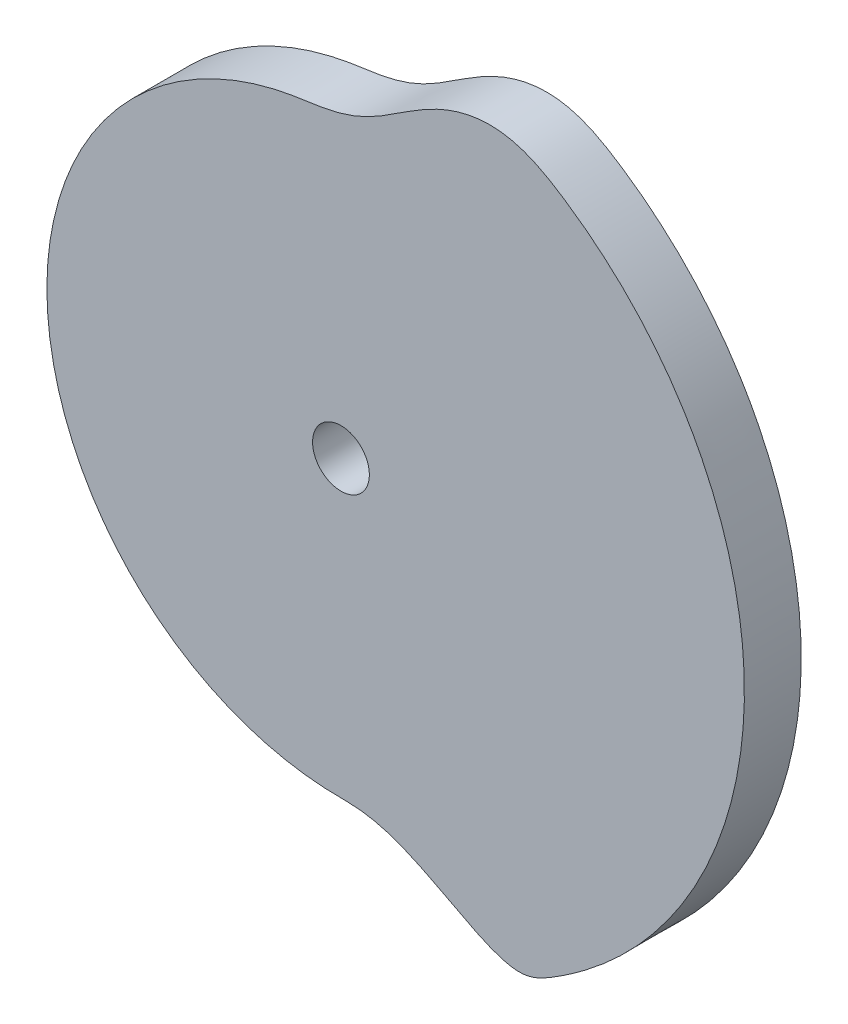
SolidWorks part; units mm, degrees
ref_plane "前视基准面" through (0, 0, 0) normal (0, 0, 1) x (1, 0, 0)
ref_plane "上视基准面" through (0, 0, 0) normal (0, 1, 0) x (1, 0, 0)
ref_plane "右视基准面" through (0, 0, 0) normal (1, 0, 0) x (0, 0, -1)
other "Configuration Table"
curve "曲线1"
sketch "草图2" plane through (0, 0, 0) normal (0, 0, 1) x (1, 0, 0)
  spline S0 degree 3 poles (121.2946, 73.8631) (120.6455, 74.9188) (119.987, 75.9687) (119.3211, 77.0105) (118.6446, 78.0488) (117.959, 79.0812) (117.2643, 80.1075) (116.5609, 81.1278) (115.8485, 82.1419) (115.1271, 83.1496) (114.3973, 84.1512) (113.6585, 85.1463) (112.9111, 86.1349) (112.1552, 87.1169) (111.3907, 88.0923) (110.6177, 89.061) (109.8363, 90.023) (109.0465, 90.978) (108.2485, 91.9262) (107.4421, 92.8673) (106.6277, 93.8014) (105.805, 94.7283) (104.9743, 95.648) (104.1356, 96.5604) (103.2891, 97.4655) (102.4346, 98.3631) (101.5723, 99.2532) (100.7023, 100.1359) (99.8246, 101.0108) (98.9394, 101.8781) (98.0465, 102.7376) (97.1463, 103.5893) (96.2386, 104.4331) (95.3236, 105.2689) (94.4013, 106.0968) (93.4719, 106.9166) (92.5353, 107.7282) (91.5916, 108.5315) (90.6412, 109.3268) (89.6836, 110.1136) (88.7193, 110.892) (87.7483, 111.662) (86.7704, 112.4234) (85.7861, 113.1765) (84.7952, 113.9208) (83.7978, 114.6563) (82.7941, 115.3833) (81.7841, 116.1014) (80.7677, 116.8105) (79.7453, 117.511) (78.7168, 118.2024) (77.6846, 118.8834) (76.653, 119.5509) (75.6258, 120.201) (74.6039, 120.8306) (73.5866, 121.4387) (72.573, 122.0241) (71.562, 122.5858) (70.5529, 123.1229) (69.5449, 123.6347) (68.5369, 124.12) (67.5284, 124.5788) (66.5183, 125.0099) (65.5061, 125.413) (64.4908, 125.7876) (63.4718, 126.1332) (62.4483, 126.4492) (61.4197, 126.7353) (60.3854, 126.9914) (59.3447, 127.2164) (58.2973, 127.4105) (57.2429, 127.5731) (56.1811, 127.7038) (55.1118, 127.8021) (54.0351, 127.8678) (52.9511, 127.9005) (51.86, 127.8999) (50.7622, 127.866) (49.6584, 127.7981) (48.5492, 127.6967) (47.4353, 127.5614) (46.3177, 127.3927) (45.1974, 127.1905) (44.0754, 126.9555) (42.9528, 126.6879) (41.8308, 126.3884) (40.7104, 126.058) (39.5929, 125.6974) (38.4793, 125.3076) (37.3706, 124.8899) (36.2678, 124.4455) (35.1718, 123.9756) (34.0833, 123.4821) (33.0031, 122.9662) (31.9315, 122.4295) (30.8689, 121.874) (29.8155, 121.3011) (28.7713, 120.7128) (27.7361, 120.1108) (26.7097, 119.4966) (25.6913, 118.8725) (24.6806, 118.2398) (23.6763, 117.6005) (22.6776, 116.9563) (21.6831, 116.3089) (20.6917, 115.6599) (19.7016, 115.0113) (18.7117, 114.3644) (17.7202, 113.7213) (16.7253, 113.0835) (15.7256, 112.453) (14.7196, 111.8316) (13.7058, 111.2211) (12.6831, 110.6237) (11.6506, 110.041) (10.6076, 109.4755) (9.5539, 108.9289) (8.4895, 108.4033) (7.4151, 107.9003) (6.3314, 107.4216) (5.2398, 106.9684) (4.1418, 106.5418) (3.0392, 106.1422) (1.934, 105.77) (0.8282, 105.4249) (-0.2761, 105.1061) (-1.3771, 104.8128) (-2.4728, 104.5433) (-3.5617, 104.2963) (-4.6422, 104.07) (-5.713, 103.8619) (-6.7729, 103.6702) (-7.8209, 103.4928) (-8.856, 103.3273) (-9.8773, 103.1717) (-10.8842, 103.0236) (-11.8756, 102.881) (-12.851, 102.7423) (-13.8092, 102.6049) (-14.7496, 102.4678) (-15.6712, 102.3287) (-16.5763, 102.186) (-17.4706, 102.0368) (-18.3604, 101.8805) (-19.2488, 101.7164) (-20.1356, 101.5444) (-21.021, 101.365) (-21.9048, 101.1777) (-22.7869, 100.9827) (-23.6673, 100.78) (-24.5458, 100.5695) (-25.4225, 100.3516) (-26.2973, 100.1258) (-27.17, 99.8926) (-28.0407, 99.6516) (-28.9092, 99.4032) (-29.7756, 99.1472) (-30.6396, 98.8834) (-31.5014, 98.6124) (-32.3607, 98.3338) (-33.2176, 98.0475) (-34.072, 97.754) (-34.9238, 97.4529) (-35.7728, 97.1445) (-36.6192, 96.8285) (-37.4628, 96.5054) (-38.3035, 96.1747) (-39.1413, 95.8368) (-39.9762, 95.4917) (-40.8079, 95.1391) (-41.6366, 94.7794) (-42.4621, 94.4124) (-43.2844, 94.0383) (-44.1034, 93.657) (-44.919, 93.2685) (-45.7312, 92.8729) (-46.54, 92.4704) (-47.3451, 92.0606) (-48.1467, 91.6441) (-48.9446, 91.2205) (-49.7387, 90.7898) (-50.5291, 90.3524) (-51.3156, 89.9079) (-52.0984, 89.4568) (-52.877, 88.9986) (-53.6516, 88.5338) (-54.4222, 88.0624) (-55.1886, 87.584) (-55.9508, 87.0991) (-56.7087, 86.6075) (-57.4623, 86.1093) (-58.2116, 85.6046) (-58.9565, 85.0934) (-59.6967, 84.5756) (-60.4325, 84.0515) (-61.1637, 83.5209) (-61.8902, 82.9839) (-62.612, 82.4407) (-63.329, 81.8911) (-64.0413, 81.3355) (-64.7486, 80.7734) (-65.451, 80.2053) (-66.1484, 79.6311) (-66.8409, 79.0509) (-67.5282, 78.4646) (-68.2103, 77.8723) (-68.8873, 77.2741) (-69.559, 76.67) (-70.2254, 76.0601) (-70.8864, 75.4443) (-71.5421, 74.8229) (-72.1923, 74.1957) (-72.837, 73.5629) (-73.4762, 72.9245) (-74.1098, 72.2805) (-74.7377, 71.631) (-75.36, 70.9761) (-75.9765, 70.3158) (-76.5872, 69.6501) (-77.1921, 68.9791) (-77.7911, 68.3029) (-78.3842, 67.6215) (-78.9713, 66.9348) (-79.5524, 66.2432) (-80.1274, 65.5464) (-80.6964, 64.8446) (-81.2593, 64.138) (-81.8158, 63.4264) (-82.3662, 62.7101) (-82.9102, 61.9889) (-83.448, 61.263) (-83.9795, 60.5324) (-84.5046, 59.7973) (-85.0231, 59.0576) (-85.5353, 58.3134) (-86.0408, 57.5647) (-86.54, 56.8118) (-87.0324, 56.0543) (-87.5183, 55.2928) (-87.9974, 54.5269) (-88.4699, 53.7569) (-88.9358, 52.9829) (-89.3946, 52.2047) (-89.8469, 51.4227) (-90.2922, 50.6366) (-90.7305, 49.8467) (-91.1622, 49.0532) (-91.5866, 48.2557) (-92.0044, 47.4546) (-92.415, 46.6499) (-92.8185, 45.8417) (-93.215, 45.03) (-93.6044, 44.2148) (-93.9867, 43.3963) (-94.3618, 42.5744) (-94.7298, 41.7494) (-95.0905, 40.9211) (-95.4439, 40.0897) (-95.7901, 39.2553) (-96.1291, 38.4179) (-96.4607, 37.5776) (-96.7849, 36.7344) (-97.1018, 35.8884) (-97.4114, 35.0397) (-97.7133, 34.1882) (-98.0079, 33.3342) (-98.2952, 32.4777) (-98.5749, 31.6187) (-98.8469, 30.7572) (-99.1117, 29.8935) (-99.3688, 29.0275) (-99.6183, 28.1592) (-99.8602, 27.2888) (-100.0944, 26.4163) (-100.3214, 25.5419) (-100.5402, 24.6654) (-100.7517, 23.7871) (-100.9555, 22.907) (-101.1515, 22.0251) (-101.3399, 21.1416) (-101.5205, 20.2564) (-101.6934, 19.3698) (-101.8586, 18.4816) (-102.016, 17.592) (-102.1656, 16.7011) (-102.3074, 15.8089) (-102.4415, 14.9155) (-102.5678, 14.021) (-102.6862, 13.1254) (-102.7968, 12.2288) (-102.8996, 11.3313) (-102.9946, 10.4329) (-103.0817, 9.5337) (-103.161, 8.6338) (-103.2324, 7.7332) (-103.296, 6.8321) (-103.3517, 5.9304) (-103.3995, 5.0283) (-103.4394, 4.1258) (-103.4715, 3.2229) (-103.4957, 2.3199) (-103.512, 1.4166) (-103.5204, 0.5133) (-103.5209, -0.3901) (-103.5137, -1.2935) (-103.4983, -2.1967) (-103.4752, -3.0999) (-103.4442, -4.0027) (-103.4055, -4.9053) (-103.3586, -5.8075) (-103.304, -6.7092) (-103.2415, -7.6104) (-103.1712, -8.5111) (-103.093, -9.4111) (-103.0068, -10.3103) (-102.9132, -11.2089) (-102.8113, -12.1065) (-102.7018, -13.0033) (-102.5844, -13.899) (-102.4592, -14.7937) (-102.3262, -15.6872) (-102.1854, -16.5795) (-102.0368, -17.4706) (-101.8805, -18.3604) (-101.7164, -19.2488) (-101.5444, -20.1356) (-101.365, -21.021) (-101.1777, -21.9048) (-100.9827, -22.7869) (-100.78, -23.6673) (-100.5695, -24.5458) (-100.3516, -25.4225) (-100.1258, -26.2973) (-99.8926, -27.17) (-99.6516, -28.0407) (-99.4032, -28.9092) (-99.1472, -29.7756) (-98.8834, -30.6396) (-98.6124, -31.5014) (-98.3338, -32.3607) (-98.0475, -33.2176) (-97.754, -34.072) (-97.4529, -34.9238) (-97.1445, -35.7728) (-96.8285, -36.6192) (-96.5054, -37.4628) (-96.1747, -38.3035) (-95.8368, -39.1413) (-95.4917, -39.9762) (-95.1391, -40.8079) (-94.7794, -41.6366) (-94.4124, -42.4621) (-94.0383, -43.2844) (-93.657, -44.1034) (-93.2685, -44.919) (-92.8729, -45.7312) (-92.4704, -46.54) (-92.0606, -47.3451) (-91.6441, -48.1467) (-91.2205, -48.9446) (-90.7898, -49.7387) (-90.3524, -50.5291) (-89.9079, -51.3156) (-89.4568, -52.0984) (-88.9986, -52.877) (-88.5338, -53.6516) (-88.0624, -54.4222) (-87.584, -55.1886) (-87.0991, -55.9508) (-86.6075, -56.7087) (-86.1093, -57.4623) (-85.6046, -58.2116) (-85.0934, -58.9565) (-84.5756, -59.6967) (-84.0515, -60.4325) (-83.5209, -61.1637) (-82.9839, -61.8902) (-82.4407, -62.612) (-81.8911, -63.329) (-81.3355, -64.0413) (-80.7734, -64.7486) (-80.2053, -65.451) (-79.6311, -66.1484) (-79.0509, -66.8409) (-78.4646, -67.5282) (-77.8723, -68.2103) (-77.2741, -68.8873) (-76.67, -69.559) (-76.0601, -70.2254) (-75.4443, -70.8864) (-74.8229, -71.5421) (-74.1957, -72.1923) (-73.5629, -72.837) (-72.9245, -73.4762) (-72.2805, -74.1098) (-71.631, -74.7377) (-70.9761, -75.36) (-70.3158, -75.9765) (-69.6501, -76.5872) (-68.9791, -77.1921) (-68.3029, -77.7911) (-67.6215, -78.3842) (-66.9348, -78.9713) (-66.2432, -79.5524) (-65.5464, -80.1274) (-64.8446, -80.6964) (-64.138, -81.2593) (-63.4264, -81.8158) (-62.7101, -82.3662) (-61.9889, -82.9102) (-61.263, -83.448) (-60.5324, -83.9795) (-59.7973, -84.5046) (-59.0576, -85.0231) (-58.3134, -85.5353) (-57.5647, -86.0408) (-56.8118, -86.54) (-56.0543, -87.0324) (-55.2928, -87.5183) (-54.5269, -87.9974) (-53.7569, -88.4699) (-52.9829, -88.9358) (-52.2047, -89.3946) (-51.4227, -89.8469) (-50.6366, -90.2922) (-49.8467, -90.7305) (-49.0532, -91.1622) (-48.2557, -91.5866) (-47.4546, -92.0044) (-46.6499, -92.415) (-45.8417, -92.8185) (-45.03, -93.215) (-44.2148, -93.6044) (-43.3963, -93.9867) (-42.5744, -94.3618) (-41.7494, -94.7298) (-40.9211, -95.0905) (-40.0897, -95.4439) (-39.2553, -95.7901) (-38.4179, -96.1291) (-37.5776, -96.4607) (-36.7344, -96.7849) (-35.8884, -97.1018) (-35.0397, -97.4114) (-34.1882, -97.7133) (-33.3342, -98.0079) (-32.4777, -98.2952) (-31.6187, -98.5749) (-30.7572, -98.8469) (-29.8935, -99.1117) (-29.0275, -99.3688) (-28.1592, -99.6183) (-27.2888, -99.8602) (-26.4163, -100.0944) (-25.5419, -100.3214) (-24.6654, -100.5402) (-23.7871, -100.7517) (-22.907, -100.9555) (-22.0251, -101.1515) (-21.1416, -101.3399) (-20.2564, -101.5205) (-19.3698, -101.6934) (-18.4816, -101.8586) (-17.592, -102.016) (-16.7011, -102.1656) (-15.8089, -102.3074) (-14.9155, -102.4415) (-14.021, -102.5678) (-13.1254, -102.6862) (-12.2288, -102.7968) (-11.3313, -102.8996) (-10.4329, -102.9946) (-9.5337, -103.0817) (-8.6338, -103.161) (-7.7332, -103.2324) (-6.8321, -103.296) (-5.9304, -103.3517) (-5.0283, -103.3995) (-4.1258, -103.4394) (-3.2229, -103.4715) (-2.3198, -103.4957) (-1.4052, -103.5122) (-0.4564, -103.5209) (0.5491, -103.5283) (1.6222, -103.5409) (2.7614, -103.5661) (3.9634, -103.6121) (5.2237, -103.6864) (6.5366, -103.7962) (7.8958, -103.948) (9.2947, -104.1462) (10.7272, -104.3947) (12.1879, -104.6952) (13.6722, -105.0488) (15.1768, -105.4551) (16.6992, -105.9135) (18.2382, -106.4221) (19.7925, -106.9793) (21.3618, -107.583) (22.9456, -108.2304) (24.5433, -108.9189) (26.154, -109.6452) (27.7765, -110.4061) (29.4094, -111.1972) (31.0505, -112.0146) (32.6973, -112.8533) (34.3468, -113.7082) (35.9959, -114.5733) (37.6409, -115.4431) (39.2779, -116.3111) (40.9029, -117.1706) (42.5114, -118.015) (44.0992, -118.8375) (45.6616, -119.6312) (47.1943, -120.3893) (48.6924, -121.1059) (50.1516, -121.7751) (51.5677, -122.3911) (52.9363, -122.9502) (54.2536, -123.4484) (55.5163, -123.8834) (56.7218, -124.2542) (57.8685, -124.5605) (58.9557, -124.8042) (59.9847, -124.9871) (60.9583, -125.1126) (61.881, -125.1847) (62.7595, -125.2064) (63.6017, -125.1814) (64.4169, -125.1118) (65.215, -124.9988) (66.0056, -124.8422) (66.7979, -124.6412) (67.6, -124.3941) (68.4184, -124.0987) (69.2585, -123.7536) (70.1244, -123.3575) (71.0191, -122.9101) (71.9451, -122.412) (72.9045, -121.8653) (73.8993, -121.2724) (74.9241, -120.6421) (75.9663, -119.9886) (77.0104, -119.3211) (78.0488, -118.6446) (79.0812, -117.959) (80.1075, -117.2643) (81.1278, -116.5609) (82.1419, -115.8485) (83.1496, -115.1271) (84.1512, -114.3973) (85.1463, -113.6585) (86.1349, -112.9111) (87.1169, -112.1552) (88.0923, -111.3907) (89.061, -110.6177) (90.023, -109.8363) (90.978, -109.0465) (91.9262, -108.2485) (92.8673, -107.4421) (93.8014, -106.6277) (94.7283, -105.805) (95.648, -104.9743) (96.5604, -104.1356) (97.4655, -103.2891) (98.3631, -102.4346) (99.2532, -101.5723) (100.1359, -100.7023) (101.0108, -99.8246) (101.8781, -98.9394) (102.7376, -98.0465) (103.5893, -97.1463) (104.4331, -96.2386) (105.2689, -95.3236) (106.0968, -94.4013) (106.9166, -93.4719) (107.7282, -92.5353) (108.5315, -91.5916) (109.3268, -90.6412) (110.1136, -89.6836) (110.892, -88.7193) (111.662, -87.7483) (112.4234, -86.7704) (113.1765, -85.7861) (113.9208, -84.7952) (114.6563, -83.7978) (115.3833, -82.7941) (116.1014, -81.784) (116.8106, -80.7677) (117.511, -79.7453) (118.2024, -78.7168) (118.8848, -77.6823) (119.5582, -76.6419) (120.2224, -75.5956) (120.8776, -74.5436) (121.5234, -73.4859) (122.1602, -72.4227) (122.7874, -71.3539) (123.4055, -70.2797) (124.014, -69.2001) (124.6133, -68.1153) (125.2029, -67.0252) (125.7829, -65.93) (126.3536, -64.8299) (126.9145, -63.7248) (127.4659, -62.6149) (128.0073, -61.5002) (128.5391, -60.3808) (129.0611, -59.2567) (129.5733, -58.1283) (130.0757, -56.9953) (130.568, -55.858) (131.0506, -54.7165) (131.5231, -53.5708) (131.9856, -52.421) (132.438, -51.2672) (132.8802, -50.1095) (133.3126, -48.9481) (133.7346, -47.7828) (134.1465, -46.614) (134.5482, -45.4416) (134.9396, -44.2657) (135.3207, -43.0864) (135.6916, -41.9039) (136.0521, -40.7182) (136.4022, -39.5294) (136.7421, -38.3376) (137.0713, -37.1428) (137.3902, -35.9453) (137.6988, -34.745) (137.9966, -33.542) (138.2842, -32.3365) (138.5611, -31.1285) (138.8273, -29.9182) (139.0832, -28.7056) (139.3284, -27.4907) (139.563, -26.2738) (139.787, -25.0549) (140.0002, -23.8341) (140.203, -22.6115) (140.3949, -21.3871) (140.5762, -20.1612) (140.7468, -18.9337) (140.9067, -17.7047) (141.0558, -16.4744) (141.1942, -15.2429) (141.3218, -14.0102) (141.4387, -12.7764) (141.5448, -11.5416) (141.6402, -10.306) (141.7247, -9.0695) (141.7984, -7.8324) (141.8614, -6.5948) (141.9135, -5.3566) (141.9549, -4.1179) (141.9854, -2.879) (142.0051, -1.6398) (142.014, -0.4005) (142.0121, 0.8388) (141.9994, 2.078) (141.9759, 3.3171) (141.9415, 4.5559) (141.8963, 5.7944) (141.8404, 7.0324) (141.7736, 8.2699) (141.696, 9.5068) (141.6077, 10.743) (141.5085, 11.9783) (141.3986, 13.2128) (141.2779, 14.4462) (141.1465, 15.6785) (141.0043, 16.9096) (140.8514, 18.1394) (140.6876, 19.3679) (140.5134, 20.5949) (140.3283, 21.8203) (140.1325, 23.044) (139.9261, 24.266) (139.709, 25.4861) (139.4813, 26.7043) (139.243, 27.9205) (138.9939, 29.1346) (138.7345, 30.3464) (138.4644, 31.5559) (138.1836, 32.763) (137.8926, 33.9676) (137.5908, 35.1697) (137.2788, 36.369) (136.9561, 37.5656) (136.623, 38.7593) (136.2797, 39.9501) (135.9258, 41.1378) (135.5616, 42.3224) (135.1871, 43.5038) (134.8025, 44.6819) (134.4073, 45.8565) (134.002, 47.0277) (133.5865, 48.1953) (133.1609, 49.3592) (132.7251, 50.5193) (132.2792, 51.6756) (131.8231, 52.828) (131.3572, 53.9764) (130.8812, 55.1206) (130.3951, 56.2606) (129.8992, 57.3964) (129.3933, 58.5277) (128.8777, 59.6547) (128.3522, 60.7771) (127.8169, 61.8948) (127.272, 63.0079) (126.7173, 64.1161) (126.1529, 65.2195) (125.579, 66.3179) (124.9955, 67.4112) (124.4025, 68.4995) (123.8, 69.5825) (123.188, 70.6601) (122.5668, 71.7324) (121.9361, 72.7993) (121.2946, 73.8631) (120.6455, 74.9188) (119.987, 75.9687) knots -0.004803 -0.003206 -0.001609 0 0.001586 0.003183 0.004781 0.006378 0.007975 0.009573 0.01117 0.012767 0.014364 0.015962 0.017559 0.019156 0.020754 0.022351 0.023948 0.025546 0.027143 0.02874 0.030338 0.031935 0.033532 0.03513 0.036727 0.038324 0.039922 0.041519 0.043116 0.044713 0.046311 0.047908 0.049505 0.051103 0.0527 0.054297 0.055895 0.057492 0.059089 0.060687 0.062284 0.063881 0.065478 0.067076 0.068673 0.07027 0.071868 0.073465 0.075062 0.07666 0.078257 0.079854 0.081441 0.083008 0.084555 0.086082 0.08759 0.089081 0.090554 0.09201 0.093452 0.094879 0.096294 0.097698 0.099092 0.100478 0.101858 0.103233 0.104606 0.105977 0.107349 0.108724 0.110102 0.111485 0.112875 0.114272 0.115678 0.117093 0.118518 0.119954 0.1214 0.122856 0.124323 0.125801 0.127288 0.128785 0.130291 0.131804 0.133325 0.134852 0.136385 0.137922 0.139463 0.141006 0.142551 0.144096 0.145642 0.147187 0.148731 0.150273 0.151812 0.153349 0.154883 0.156415 0.157944 0.159472 0.160997 0.162521 0.164044 0.165567 0.16709 0.168614 0.170139 0.171666 0.173194 0.174723 0.176253 0.177783 0.179313 0.18084 0.182364 0.183883 0.185395 0.186898 0.188391 0.189873 0.191342 0.192797 0.194236 0.195659 0.197065 0.198454 0.199824 0.201175 0.202507 0.203819 0.20511 0.20638 0.207628 0.208853 0.210055 0.211232 0.212396 0.213561 0.214725 0.215889 0.217054 0.218218 0.219382 0.220547 0.221711 0.222875 0.22404 0.225204 0.226368 0.227533 0.228697 0.229862 0.231026 0.23219 0.233355 0.234519 0.235683 0.236848 0.238012 0.239176 0.240341 0.241505 0.24267 0.243834 0.244998 0.246163 0.247327 0.248491 0.249656 0.25082 0.251984 0.253149 0.254313 0.255477 0.256642 0.257806 0.258971 0.260135 0.261299 0.262464 0.263628 0.264792 0.265957 0.267121 0.268285 0.26945 0.270614 0.271779 0.272943 0.274107 0.275272 0.276436 0.2776 0.278765 0.279929 0.281093 0.282258 0.283422 0.284587 0.285751 0.286915 0.28808 0.289244 0.290408 0.291573 0.292737 0.293901 0.295066 0.29623 0.297395 0.298559 0.299723 0.300888 0.302052 0.303216 0.304381 0.305545 0.306709 0.307874 0.309038 0.310202 0.311367 0.312531 0.313695 0.31486 0.316024 0.317189 0.318353 0.319517 0.320682 0.321846 0.32301 0.324175 0.325339 0.326503 0.327668 0.328832 0.329997 0.331161 0.332325 0.33349 0.334654 0.335818 0.336983 0.338147 0.339311 0.340476 0.34164 0.342804 0.343969 0.345133 0.346298 0.347462 0.348626 0.349791 0.350955 0.352119 0.353284 0.354448 0.355613 0.356777 0.357941 0.359106 0.36027 0.361434 0.362599 0.363763 0.364927 0.366092 0.367256 0.36842 0.369585 0.370749 0.371914 0.373078 0.374242 0.375407 0.376571 0.377735 0.3789 0.380064 0.381228 0.382393 0.383557 0.384722 0.385886 0.38705 0.388215 0.389379 0.390543 0.391708 0.392872 0.394036 0.395201 0.396365 0.397529 0.398694 0.399858 0.401023 0.402187 0.403351 0.404516 0.40568 0.406844 0.408009 0.409173 0.410337 0.411502 0.412666 0.41383 0.414995 0.416159 0.417324 0.418488 0.419652 0.420817 0.421981 0.423145 0.42431 0.425474 0.426638 0.427803 0.428967 0.430132 0.431296 0.43246 0.433625 0.434789 0.435953 0.437118 0.438282 0.439446 0.440611 0.441775 0.44294 0.444104 0.445268 0.446433 0.447597 0.448761 0.449926 0.45109 0.452254 0.453419 0.454583 0.455747 0.456912 0.458076 0.459241 0.460405 0.461569 0.462734 0.463898 0.465062 0.466227 0.467391 0.468555 0.46972 0.470884 0.472048 0.473213 0.474377 0.475542 0.476706 0.47787 0.479035 0.480199 0.481363 0.482528 0.483692 0.484856 0.486021 0.487185 0.48835 0.489514 0.490678 0.491843 0.493007 0.494171 0.495336 0.4965 0.497665 0.498829 0.499993 0.501158 0.502322 0.503486 0.504651 0.505815 0.506979 0.508144 0.509308 0.510472 0.511637 0.512801 0.513965 0.51513 0.516294 0.517459 0.518623 0.519787 0.520952 0.522116 0.52328 0.524445 0.525609 0.526774 0.527938 0.529102 0.530267 0.531431 0.532595 0.53376 0.534924 0.536088 0.537253 0.538417 0.539581 0.540746 0.54191 0.543074 0.544239 0.545403 0.546568 0.547732 0.548896 0.550061 0.551225 0.552389 0.553554 0.554718 0.555883 0.557047 0.558211 0.559376 0.56054 0.561704 0.562869 0.564033 0.565197 0.566362 0.567526 0.56869 0.569855 0.571019 0.572184 0.573348 0.574512 0.575677 0.576841 0.578005 0.57917 0.580334 0.581498 0.582663 0.583827 0.584991 0.586156 0.58732 0.588485 0.589649 0.590813 0.591978 0.593142 0.594306 0.595471 0.596635 0.597799 0.598964 0.600128 0.601293 0.602457 0.603621 0.604786 0.60595 0.607115 0.608323 0.609619 0.611003 0.612472 0.614024 0.615654 0.617354 0.619118 0.620941 0.622816 0.624739 0.626706 0.628715 0.630764 0.632853 0.634981 0.637149 0.639354 0.641597 0.643875 0.646186 0.648526 0.650891 0.653275 0.655672 0.658075 0.660476 0.662867 0.665239 0.667584 0.669891 0.672153 0.67436 0.676503 0.678574 0.680567 0.682474 0.68429 0.686012 0.687637 0.689166 0.6906 0.691944 0.693205 0.694394 0.695521 0.696601 0.69765 0.698683 0.699717 0.700765 0.701843 0.70296 0.704128 0.705353 0.706641 0.707996 0.709418 0.710911 0.712473 0.71407 0.715668 0.717265 0.718862 0.720459 0.722057 0.723654 0.725251 0.726849 0.728446 0.730043 0.731641 0.733238 0.734835 0.736433 0.73803 0.739627 0.741225 0.742822 0.744419 0.746017 0.747614 0.749211 0.750808 0.752406 0.754003 0.7556 0.757198 0.758795 0.760392 0.76199 0.763587 0.765184 0.766781 0.768379 0.769976 0.771573 0.773171 0.774768 0.776365 0.777963 0.77956 0.781157 0.782755 0.784352 0.785949 0.787547 0.789144 0.790741 0.792338 0.793936 0.795533 0.79713 0.798728 0.800325 0.801922 0.80352 0.805117 0.806714 0.808312 0.809909 0.811506 0.813103 0.814701 0.816298 0.817895 0.819493 0.82109 0.822687 0.824285 0.825882 0.827479 0.829077 0.830674 0.832271 0.833869 0.835466 0.837063 0.83866 0.840258 0.841855 0.843452 0.84505 0.846647 0.848244 0.849842 0.851439 0.853036 0.854633 0.856231 0.857828 0.859425 0.861023 0.86262 0.864217 0.865815 0.867412 0.869009 0.870607 0.872204 0.873801 0.875399 0.876996 0.878593 0.88019 0.881788 0.883385 0.884982 0.88658 0.888177 0.889774 0.891372 0.892969 0.894566 0.896164 0.897761 0.899358 0.900956 0.902553 0.90415 0.905747 0.907345 0.908942 0.910539 0.912137 0.913734 0.915331 0.916929 0.918526 0.920123 0.921721 0.923318 0.924915 0.926512 0.92811 0.929707 0.931304 0.932902 0.934499 0.936096 0.937694 0.939291 0.940888 0.942486 0.944083 0.94568 0.947277 0.948875 0.950472 0.952069 0.953667 0.955264 0.956861 0.958459 0.960056 0.961653 0.963251 0.964848 0.966445 0.968042 0.96964 0.971237 0.972834 0.974432 0.976029 0.977626 0.979224 0.980821 0.982418 0.984016 0.985613 0.98721 0.988808 0.990405 0.992002 0.993599 0.995197 0.996794 0.998391 1 1.001586 1.003183 1.004781 only from (120.6409, 74.9228) to (120.6409, 74.9228) construction
  spline S1 degree 3 poles (121.2946, 73.8631) (120.6455, 74.9188) (119.987, 75.9687) (119.3211, 77.0105) (118.6446, 78.0488) (117.959, 79.0812) (117.2643, 80.1075) (116.5609, 81.1278) (115.8485, 82.1419) (115.1271, 83.1496) (114.3973, 84.1512) (113.6585, 85.1463) (112.9111, 86.1349) (112.1552, 87.1169) (111.3907, 88.0923) (110.6177, 89.061) (109.8363, 90.023) (109.0465, 90.978) (108.2485, 91.9262) (107.4421, 92.8673) (106.6277, 93.8014) (105.805, 94.7283) (104.9743, 95.648) (104.1356, 96.5604) (103.2891, 97.4655) (102.4346, 98.3631) (101.5723, 99.2532) (100.7023, 100.1359) (99.8246, 101.0108) (98.9394, 101.8781) (98.0465, 102.7376) (97.1463, 103.5893) (96.2386, 104.4331) (95.3236, 105.2689) (94.4013, 106.0968) (93.4719, 106.9166) (92.5353, 107.7282) (91.5916, 108.5315) (90.6412, 109.3268) (89.6836, 110.1136) (88.7193, 110.892) (87.7483, 111.662) (86.7704, 112.4234) (85.7861, 113.1765) (84.7952, 113.9208) (83.7978, 114.6563) (82.7941, 115.3833) (81.7841, 116.1014) (80.7677, 116.8105) (79.7453, 117.511) (78.7168, 118.2024) (77.6846, 118.8834) (76.653, 119.5509) (75.6258, 120.201) (74.6039, 120.8306) (73.5866, 121.4387) (72.573, 122.0241) (71.562, 122.5858) (70.5529, 123.1229) (69.5449, 123.6347) (68.5369, 124.12) (67.5284, 124.5788) (66.5183, 125.0099) (65.5061, 125.413) (64.4908, 125.7876) (63.4718, 126.1332) (62.4483, 126.4492) (61.4197, 126.7353) (60.3854, 126.9914) (59.3447, 127.2164) (58.2973, 127.4105) (57.2429, 127.5731) (56.1811, 127.7038) (55.1118, 127.8021) (54.0351, 127.8678) (52.9511, 127.9005) (51.86, 127.8999) (50.7622, 127.866) (49.6584, 127.7981) (48.5492, 127.6967) (47.4353, 127.5614) (46.3177, 127.3927) (45.1974, 127.1905) (44.0754, 126.9555) (42.9528, 126.6879) (41.8308, 126.3884) (40.7104, 126.058) (39.5929, 125.6974) (38.4793, 125.3076) (37.3706, 124.8899) (36.2678, 124.4455) (35.1718, 123.9756) (34.0833, 123.4821) (33.0031, 122.9662) (31.9315, 122.4295) (30.8689, 121.874) (29.8155, 121.3011) (28.7713, 120.7128) (27.7361, 120.1108) (26.7097, 119.4966) (25.6913, 118.8725) (24.6806, 118.2398) (23.6763, 117.6005) (22.6776, 116.9563) (21.6831, 116.3089) (20.6917, 115.6599) (19.7016, 115.0113) (18.7117, 114.3644) (17.7202, 113.7213) (16.7253, 113.0835) (15.7256, 112.453) (14.7196, 111.8316) (13.7058, 111.2211) (12.6831, 110.6237) (11.6506, 110.041) (10.6076, 109.4755) (9.5539, 108.9289) (8.4895, 108.4033) (7.4151, 107.9003) (6.3314, 107.4216) (5.2398, 106.9684) (4.1418, 106.5418) (3.0392, 106.1422) (1.934, 105.77) (0.8282, 105.4249) (-0.2761, 105.1061) (-1.3771, 104.8128) (-2.4728, 104.5433) (-3.5617, 104.2963) (-4.6422, 104.07) (-5.713, 103.8619) (-6.7729, 103.6702) (-7.8209, 103.4928) (-8.856, 103.3273) (-9.8773, 103.1717) (-10.8842, 103.0236) (-11.8756, 102.881) (-12.851, 102.7423) (-13.8092, 102.6049) (-14.7496, 102.4678) (-15.6712, 102.3287) (-16.5763, 102.186) (-17.4706, 102.0368) (-18.3604, 101.8805) (-19.2488, 101.7164) (-20.1356, 101.5444) (-21.021, 101.365) (-21.9048, 101.1777) (-22.7869, 100.9827) (-23.6673, 100.78) (-24.5458, 100.5695) (-25.4225, 100.3516) (-26.2973, 100.1258) (-27.17, 99.8926) (-28.0407, 99.6516) (-28.9092, 99.4032) (-29.7756, 99.1472) (-30.6396, 98.8834) (-31.5014, 98.6124) (-32.3607, 98.3338) (-33.2176, 98.0475) (-34.072, 97.754) (-34.9238, 97.4529) (-35.7728, 97.1445) (-36.6192, 96.8285) (-37.4628, 96.5054) (-38.3035, 96.1747) (-39.1413, 95.8368) (-39.9762, 95.4917) (-40.8079, 95.1391) (-41.6366, 94.7794) (-42.4621, 94.4124) (-43.2844, 94.0383) (-44.1034, 93.657) (-44.919, 93.2685) (-45.7312, 92.8729) (-46.54, 92.4704) (-47.3451, 92.0606) (-48.1467, 91.6441) (-48.9446, 91.2205) (-49.7387, 90.7898) (-50.5291, 90.3524) (-51.3156, 89.9079) (-52.0984, 89.4568) (-52.877, 88.9986) (-53.6516, 88.5338) (-54.4222, 88.0624) (-55.1886, 87.584) (-55.9508, 87.0991) (-56.7087, 86.6075) (-57.4623, 86.1093) (-58.2116, 85.6046) (-58.9565, 85.0934) (-59.6967, 84.5756) (-60.4325, 84.0515) (-61.1637, 83.5209) (-61.8902, 82.9839) (-62.612, 82.4407) (-63.329, 81.8911) (-64.0413, 81.3355) (-64.7486, 80.7734) (-65.451, 80.2053) (-66.1484, 79.6311) (-66.8409, 79.0509) (-67.5282, 78.4646) (-68.2103, 77.8723) (-68.8873, 77.2741) (-69.559, 76.67) (-70.2254, 76.0601) (-70.8864, 75.4443) (-71.5421, 74.8229) (-72.1923, 74.1957) (-72.837, 73.5629) (-73.4762, 72.9245) (-74.1098, 72.2805) (-74.7377, 71.631) (-75.36, 70.9761) (-75.9765, 70.3158) (-76.5872, 69.6501) (-77.1921, 68.9791) (-77.7911, 68.3029) (-78.3842, 67.6215) (-78.9713, 66.9348) (-79.5524, 66.2432) (-80.1274, 65.5464) (-80.6964, 64.8446) (-81.2593, 64.138) (-81.8158, 63.4264) (-82.3662, 62.7101) (-82.9102, 61.9889) (-83.448, 61.263) (-83.9795, 60.5324) (-84.5046, 59.7973) (-85.0231, 59.0576) (-85.5353, 58.3134) (-86.0408, 57.5647) (-86.54, 56.8118) (-87.0324, 56.0543) (-87.5183, 55.2928) (-87.9974, 54.5269) (-88.4699, 53.7569) (-88.9358, 52.9829) (-89.3946, 52.2047) (-89.8469, 51.4227) (-90.2922, 50.6366) (-90.7305, 49.8467) (-91.1622, 49.0532) (-91.5866, 48.2557) (-92.0044, 47.4546) (-92.415, 46.6499) (-92.8185, 45.8417) (-93.215, 45.03) (-93.6044, 44.2148) (-93.9867, 43.3963) (-94.3618, 42.5744) (-94.7298, 41.7494) (-95.0905, 40.9211) (-95.4439, 40.0897) (-95.7901, 39.2553) (-96.1291, 38.4179) (-96.4607, 37.5776) (-96.7849, 36.7344) (-97.1018, 35.8884) (-97.4114, 35.0397) (-97.7133, 34.1882) (-98.0079, 33.3342) (-98.2952, 32.4777) (-98.5749, 31.6187) (-98.8469, 30.7572) (-99.1117, 29.8935) (-99.3688, 29.0275) (-99.6183, 28.1592) (-99.8602, 27.2888) (-100.0944, 26.4163) (-100.3214, 25.5419) (-100.5402, 24.6654) (-100.7517, 23.7871) (-100.9555, 22.907) (-101.1515, 22.0251) (-101.3399, 21.1416) (-101.5205, 20.2564) (-101.6934, 19.3698) (-101.8586, 18.4816) (-102.016, 17.592) (-102.1656, 16.7011) (-102.3074, 15.8089) (-102.4415, 14.9155) (-102.5678, 14.021) (-102.6862, 13.1254) (-102.7968, 12.2288) (-102.8996, 11.3313) (-102.9946, 10.4329) (-103.0817, 9.5337) (-103.161, 8.6338) (-103.2324, 7.7332) (-103.296, 6.8321) (-103.3517, 5.9304) (-103.3995, 5.0283) (-103.4394, 4.1258) (-103.4715, 3.2229) (-103.4957, 2.3199) (-103.512, 1.4166) (-103.5204, 0.5133) (-103.5209, -0.3901) (-103.5137, -1.2935) (-103.4983, -2.1967) (-103.4752, -3.0999) (-103.4442, -4.0027) (-103.4055, -4.9053) (-103.3586, -5.8075) (-103.304, -6.7092) (-103.2415, -7.6104) (-103.1712, -8.5111) (-103.093, -9.4111) (-103.0068, -10.3103) (-102.9132, -11.2089) (-102.8113, -12.1065) (-102.7018, -13.0033) (-102.5844, -13.899) (-102.4592, -14.7937) (-102.3262, -15.6872) (-102.1854, -16.5795) (-102.0368, -17.4706) (-101.8805, -18.3604) (-101.7164, -19.2488) (-101.5444, -20.1356) (-101.365, -21.021) (-101.1777, -21.9048) (-100.9827, -22.7869) (-100.78, -23.6673) (-100.5695, -24.5458) (-100.3516, -25.4225) (-100.1258, -26.2973) (-99.8926, -27.17) (-99.6516, -28.0407) (-99.4032, -28.9092) (-99.1472, -29.7756) (-98.8834, -30.6396) (-98.6124, -31.5014) (-98.3338, -32.3607) (-98.0475, -33.2176) (-97.754, -34.072) (-97.4529, -34.9238) (-97.1445, -35.7728) (-96.8285, -36.6192) (-96.5054, -37.4628) (-96.1747, -38.3035) (-95.8368, -39.1413) (-95.4917, -39.9762) (-95.1391, -40.8079) (-94.7794, -41.6366) (-94.4124, -42.4621) (-94.0383, -43.2844) (-93.657, -44.1034) (-93.2685, -44.919) (-92.8729, -45.7312) (-92.4704, -46.54) (-92.0606, -47.3451) (-91.6441, -48.1467) (-91.2205, -48.9446) (-90.7898, -49.7387) (-90.3524, -50.5291) (-89.9079, -51.3156) (-89.4568, -52.0984) (-88.9986, -52.877) (-88.5338, -53.6516) (-88.0624, -54.4222) (-87.584, -55.1886) (-87.0991, -55.9508) (-86.6075, -56.7087) (-86.1093, -57.4623) (-85.6046, -58.2116) (-85.0934, -58.9565) (-84.5756, -59.6967) (-84.0515, -60.4325) (-83.5209, -61.1637) (-82.9839, -61.8902) (-82.4407, -62.612) (-81.8911, -63.329) (-81.3355, -64.0413) (-80.7734, -64.7486) (-80.2053, -65.451) (-79.6311, -66.1484) (-79.0509, -66.8409) (-78.4646, -67.5282) (-77.8723, -68.2103) (-77.2741, -68.8873) (-76.67, -69.559) (-76.0601, -70.2254) (-75.4443, -70.8864) (-74.8229, -71.5421) (-74.1957, -72.1923) (-73.5629, -72.837) (-72.9245, -73.4762) (-72.2805, -74.1098) (-71.631, -74.7377) (-70.9761, -75.36) (-70.3158, -75.9765) (-69.6501, -76.5872) (-68.9791, -77.1921) (-68.3029, -77.7911) (-67.6215, -78.3842) (-66.9348, -78.9713) (-66.2432, -79.5524) (-65.5464, -80.1274) (-64.8446, -80.6964) (-64.138, -81.2593) (-63.4264, -81.8158) (-62.7101, -82.3662) (-61.9889, -82.9102) (-61.263, -83.448) (-60.5324, -83.9795) (-59.7973, -84.5046) (-59.0576, -85.0231) (-58.3134, -85.5353) (-57.5647, -86.0408) (-56.8118, -86.54) (-56.0543, -87.0324) (-55.2928, -87.5183) (-54.5269, -87.9974) (-53.7569, -88.4699) (-52.9829, -88.9358) (-52.2047, -89.3946) (-51.4227, -89.8469) (-50.6366, -90.2922) (-49.8467, -90.7305) (-49.0532, -91.1622) (-48.2557, -91.5866) (-47.4546, -92.0044) (-46.6499, -92.415) (-45.8417, -92.8185) (-45.03, -93.215) (-44.2148, -93.6044) (-43.3963, -93.9867) (-42.5744, -94.3618) (-41.7494, -94.7298) (-40.9211, -95.0905) (-40.0897, -95.4439) (-39.2553, -95.7901) (-38.4179, -96.1291) (-37.5776, -96.4607) (-36.7344, -96.7849) (-35.8884, -97.1018) (-35.0397, -97.4114) (-34.1882, -97.7133) (-33.3342, -98.0079) (-32.4777, -98.2952) (-31.6187, -98.5749) (-30.7572, -98.8469) (-29.8935, -99.1117) (-29.0275, -99.3688) (-28.1592, -99.6183) (-27.2888, -99.8602) (-26.4163, -100.0944) (-25.5419, -100.3214) (-24.6654, -100.5402) (-23.7871, -100.7517) (-22.907, -100.9555) (-22.0251, -101.1515) (-21.1416, -101.3399) (-20.2564, -101.5205) (-19.3698, -101.6934) (-18.4816, -101.8586) (-17.592, -102.016) (-16.7011, -102.1656) (-15.8089, -102.3074) (-14.9155, -102.4415) (-14.021, -102.5678) (-13.1254, -102.6862) (-12.2288, -102.7968) (-11.3313, -102.8996) (-10.4329, -102.9946) (-9.5337, -103.0817) (-8.6338, -103.161) (-7.7332, -103.2324) (-6.8321, -103.296) (-5.9304, -103.3517) (-5.0283, -103.3995) (-4.1258, -103.4394) (-3.2229, -103.4715) (-2.3198, -103.4957) (-1.4052, -103.5122) (-0.4564, -103.5209) (0.5491, -103.5283) (1.6222, -103.5409) (2.7614, -103.5661) (3.9634, -103.6121) (5.2237, -103.6864) (6.5366, -103.7962) (7.8958, -103.948) (9.2947, -104.1462) (10.7272, -104.3947) (12.1879, -104.6952) (13.6722, -105.0488) (15.1768, -105.4551) (16.6992, -105.9135) (18.2382, -106.4221) (19.7925, -106.9793) (21.3618, -107.583) (22.9456, -108.2304) (24.5433, -108.9189) (26.154, -109.6452) (27.7765, -110.4061) (29.4094, -111.1972) (31.0505, -112.0146) (32.6973, -112.8533) (34.3468, -113.7082) (35.9959, -114.5733) (37.6409, -115.4431) (39.2779, -116.3111) (40.9029, -117.1706) (42.5114, -118.015) (44.0992, -118.8375) (45.6616, -119.6312) (47.1943, -120.3893) (48.6924, -121.1059) (50.1516, -121.7751) (51.5677, -122.3911) (52.9363, -122.9502) (54.2536, -123.4484) (55.5163, -123.8834) (56.7218, -124.2542) (57.8685, -124.5605) (58.9557, -124.8042) (59.9847, -124.9871) (60.9583, -125.1126) (61.881, -125.1847) (62.7595, -125.2064) (63.6017, -125.1814) (64.4169, -125.1118) (65.215, -124.9988) (66.0056, -124.8422) (66.7979, -124.6412) (67.6, -124.3941) (68.4184, -124.0987) (69.2585, -123.7536) (70.1244, -123.3575) (71.0191, -122.9101) (71.9451, -122.412) (72.9045, -121.8653) (73.8993, -121.2724) (74.9241, -120.6421) (75.9663, -119.9886) (77.0104, -119.3211) (78.0488, -118.6446) (79.0812, -117.959) (80.1075, -117.2643) (81.1278, -116.5609) (82.1419, -115.8485) (83.1496, -115.1271) (84.1512, -114.3973) (85.1463, -113.6585) (86.1349, -112.9111) (87.1169, -112.1552) (88.0923, -111.3907) (89.061, -110.6177) (90.023, -109.8363) (90.978, -109.0465) (91.9262, -108.2485) (92.8673, -107.4421) (93.8014, -106.6277) (94.7283, -105.805) (95.648, -104.9743) (96.5604, -104.1356) (97.4655, -103.2891) (98.3631, -102.4346) (99.2532, -101.5723) (100.1359, -100.7023) (101.0108, -99.8246) (101.8781, -98.9394) (102.7376, -98.0465) (103.5893, -97.1463) (104.4331, -96.2386) (105.2689, -95.3236) (106.0968, -94.4013) (106.9166, -93.4719) (107.7282, -92.5353) (108.5315, -91.5916) (109.3268, -90.6412) (110.1136, -89.6836) (110.892, -88.7193) (111.662, -87.7483) (112.4234, -86.7704) (113.1765, -85.7861) (113.9208, -84.7952) (114.6563, -83.7978) (115.3833, -82.7941) (116.1014, -81.784) (116.8106, -80.7677) (117.511, -79.7453) (118.2024, -78.7168) (118.8848, -77.6823) (119.5582, -76.6419) (120.2224, -75.5956) (120.8776, -74.5436) (121.5234, -73.4859) (122.1602, -72.4227) (122.7874, -71.3539) (123.4055, -70.2797) (124.014, -69.2001) (124.6133, -68.1153) (125.2029, -67.0252) (125.7829, -65.93) (126.3536, -64.8299) (126.9145, -63.7248) (127.4659, -62.6149) (128.0073, -61.5002) (128.5391, -60.3808) (129.0611, -59.2567) (129.5733, -58.1283) (130.0757, -56.9953) (130.568, -55.858) (131.0506, -54.7165) (131.5231, -53.5708) (131.9856, -52.421) (132.438, -51.2672) (132.8802, -50.1095) (133.3126, -48.9481) (133.7346, -47.7828) (134.1465, -46.614) (134.5482, -45.4416) (134.9396, -44.2657) (135.3207, -43.0864) (135.6916, -41.9039) (136.0521, -40.7182) (136.4022, -39.5294) (136.7421, -38.3376) (137.0713, -37.1428) (137.3902, -35.9453) (137.6988, -34.745) (137.9966, -33.542) (138.2842, -32.3365) (138.5611, -31.1285) (138.8273, -29.9182) (139.0832, -28.7056) (139.3284, -27.4907) (139.563, -26.2738) (139.787, -25.0549) (140.0002, -23.8341) (140.203, -22.6115) (140.3949, -21.3871) (140.5762, -20.1612) (140.7468, -18.9337) (140.9067, -17.7047) (141.0558, -16.4744) (141.1942, -15.2429) (141.3218, -14.0102) (141.4387, -12.7764) (141.5448, -11.5416) (141.6402, -10.306) (141.7247, -9.0695) (141.7984, -7.8324) (141.8614, -6.5948) (141.9135, -5.3566) (141.9549, -4.1179) (141.9854, -2.879) (142.0051, -1.6398) (142.014, -0.4005) (142.0121, 0.8388) (141.9994, 2.078) (141.9759, 3.3171) (141.9415, 4.5559) (141.8963, 5.7944) (141.8404, 7.0324) (141.7736, 8.2699) (141.696, 9.5068) (141.6077, 10.743) (141.5085, 11.9783) (141.3986, 13.2128) (141.2779, 14.4462) (141.1465, 15.6785) (141.0043, 16.9096) (140.8514, 18.1394) (140.6876, 19.3679) (140.5134, 20.5949) (140.3283, 21.8203) (140.1325, 23.044) (139.9261, 24.266) (139.709, 25.4861) (139.4813, 26.7043) (139.243, 27.9205) (138.9939, 29.1346) (138.7345, 30.3464) (138.4644, 31.5559) (138.1836, 32.763) (137.8926, 33.9676) (137.5908, 35.1697) (137.2788, 36.369) (136.9561, 37.5656) (136.623, 38.7593) (136.2797, 39.9501) (135.9258, 41.1378) (135.5616, 42.3224) (135.1871, 43.5038) (134.8025, 44.6819) (134.4073, 45.8565) (134.002, 47.0277) (133.5865, 48.1953) (133.1609, 49.3592) (132.7251, 50.5193) (132.2792, 51.6756) (131.8231, 52.828) (131.3572, 53.9764) (130.8812, 55.1206) (130.3951, 56.2606) (129.8992, 57.3964) (129.3933, 58.5277) (128.8777, 59.6547) (128.3522, 60.7771) (127.8169, 61.8948) (127.272, 63.0079) (126.7173, 64.1161) (126.1529, 65.2195) (125.579, 66.3179) (124.9955, 67.4112) (124.4025, 68.4995) (123.8, 69.5825) (123.188, 70.6601) (122.5668, 71.7324) (121.9361, 72.7993) (121.2946, 73.8631) (120.6455, 74.9188) (119.987, 75.9687) knots -0.004803 -0.003206 -0.001609 0 0.001586 0.003183 0.004781 0.006378 0.007975 0.009573 0.01117 0.012767 0.014364 0.015962 0.017559 0.019156 0.020754 0.022351 0.023948 0.025546 0.027143 0.02874 0.030338 0.031935 0.033532 0.03513 0.036727 0.038324 0.039922 0.041519 0.043116 0.044713 0.046311 0.047908 0.049505 0.051103 0.0527 0.054297 0.055895 0.057492 0.059089 0.060687 0.062284 0.063881 0.065478 0.067076 0.068673 0.07027 0.071868 0.073465 0.075062 0.07666 0.078257 0.079854 0.081441 0.083008 0.084555 0.086082 0.08759 0.089081 0.090554 0.09201 0.093452 0.094879 0.096294 0.097698 0.099092 0.100478 0.101858 0.103233 0.104606 0.105977 0.107349 0.108724 0.110102 0.111485 0.112875 0.114272 0.115678 0.117093 0.118518 0.119954 0.1214 0.122856 0.124323 0.125801 0.127288 0.128785 0.130291 0.131804 0.133325 0.134852 0.136385 0.137922 0.139463 0.141006 0.142551 0.144096 0.145642 0.147187 0.148731 0.150273 0.151812 0.153349 0.154883 0.156415 0.157944 0.159472 0.160997 0.162521 0.164044 0.165567 0.16709 0.168614 0.170139 0.171666 0.173194 0.174723 0.176253 0.177783 0.179313 0.18084 0.182364 0.183883 0.185395 0.186898 0.188391 0.189873 0.191342 0.192797 0.194236 0.195659 0.197065 0.198454 0.199824 0.201175 0.202507 0.203819 0.20511 0.20638 0.207628 0.208853 0.210055 0.211232 0.212396 0.213561 0.214725 0.215889 0.217054 0.218218 0.219382 0.220547 0.221711 0.222875 0.22404 0.225204 0.226368 0.227533 0.228697 0.229862 0.231026 0.23219 0.233355 0.234519 0.235683 0.236848 0.238012 0.239176 0.240341 0.241505 0.24267 0.243834 0.244998 0.246163 0.247327 0.248491 0.249656 0.25082 0.251984 0.253149 0.254313 0.255477 0.256642 0.257806 0.258971 0.260135 0.261299 0.262464 0.263628 0.264792 0.265957 0.267121 0.268285 0.26945 0.270614 0.271779 0.272943 0.274107 0.275272 0.276436 0.2776 0.278765 0.279929 0.281093 0.282258 0.283422 0.284587 0.285751 0.286915 0.28808 0.289244 0.290408 0.291573 0.292737 0.293901 0.295066 0.29623 0.297395 0.298559 0.299723 0.300888 0.302052 0.303216 0.304381 0.305545 0.306709 0.307874 0.309038 0.310202 0.311367 0.312531 0.313695 0.31486 0.316024 0.317189 0.318353 0.319517 0.320682 0.321846 0.32301 0.324175 0.325339 0.326503 0.327668 0.328832 0.329997 0.331161 0.332325 0.33349 0.334654 0.335818 0.336983 0.338147 0.339311 0.340476 0.34164 0.342804 0.343969 0.345133 0.346298 0.347462 0.348626 0.349791 0.350955 0.352119 0.353284 0.354448 0.355613 0.356777 0.357941 0.359106 0.36027 0.361434 0.362599 0.363763 0.364927 0.366092 0.367256 0.36842 0.369585 0.370749 0.371914 0.373078 0.374242 0.375407 0.376571 0.377735 0.3789 0.380064 0.381228 0.382393 0.383557 0.384722 0.385886 0.38705 0.388215 0.389379 0.390543 0.391708 0.392872 0.394036 0.395201 0.396365 0.397529 0.398694 0.399858 0.401023 0.402187 0.403351 0.404516 0.40568 0.406844 0.408009 0.409173 0.410337 0.411502 0.412666 0.41383 0.414995 0.416159 0.417324 0.418488 0.419652 0.420817 0.421981 0.423145 0.42431 0.425474 0.426638 0.427803 0.428967 0.430132 0.431296 0.43246 0.433625 0.434789 0.435953 0.437118 0.438282 0.439446 0.440611 0.441775 0.44294 0.444104 0.445268 0.446433 0.447597 0.448761 0.449926 0.45109 0.452254 0.453419 0.454583 0.455747 0.456912 0.458076 0.459241 0.460405 0.461569 0.462734 0.463898 0.465062 0.466227 0.467391 0.468555 0.46972 0.470884 0.472048 0.473213 0.474377 0.475542 0.476706 0.47787 0.479035 0.480199 0.481363 0.482528 0.483692 0.484856 0.486021 0.487185 0.48835 0.489514 0.490678 0.491843 0.493007 0.494171 0.495336 0.4965 0.497665 0.498829 0.499993 0.501158 0.502322 0.503486 0.504651 0.505815 0.506979 0.508144 0.509308 0.510472 0.511637 0.512801 0.513965 0.51513 0.516294 0.517459 0.518623 0.519787 0.520952 0.522116 0.52328 0.524445 0.525609 0.526774 0.527938 0.529102 0.530267 0.531431 0.532595 0.53376 0.534924 0.536088 0.537253 0.538417 0.539581 0.540746 0.54191 0.543074 0.544239 0.545403 0.546568 0.547732 0.548896 0.550061 0.551225 0.552389 0.553554 0.554718 0.555883 0.557047 0.558211 0.559376 0.56054 0.561704 0.562869 0.564033 0.565197 0.566362 0.567526 0.56869 0.569855 0.571019 0.572184 0.573348 0.574512 0.575677 0.576841 0.578005 0.57917 0.580334 0.581498 0.582663 0.583827 0.584991 0.586156 0.58732 0.588485 0.589649 0.590813 0.591978 0.593142 0.594306 0.595471 0.596635 0.597799 0.598964 0.600128 0.601293 0.602457 0.603621 0.604786 0.60595 0.607115 0.608323 0.609619 0.611003 0.612472 0.614024 0.615654 0.617354 0.619118 0.620941 0.622816 0.624739 0.626706 0.628715 0.630764 0.632853 0.634981 0.637149 0.639354 0.641597 0.643875 0.646186 0.648526 0.650891 0.653275 0.655672 0.658075 0.660476 0.662867 0.665239 0.667584 0.669891 0.672153 0.67436 0.676503 0.678574 0.680567 0.682474 0.68429 0.686012 0.687637 0.689166 0.6906 0.691944 0.693205 0.694394 0.695521 0.696601 0.69765 0.698683 0.699717 0.700765 0.701843 0.70296 0.704128 0.705353 0.706641 0.707996 0.709418 0.710911 0.712473 0.71407 0.715668 0.717265 0.718862 0.720459 0.722057 0.723654 0.725251 0.726849 0.728446 0.730043 0.731641 0.733238 0.734835 0.736433 0.73803 0.739627 0.741225 0.742822 0.744419 0.746017 0.747614 0.749211 0.750808 0.752406 0.754003 0.7556 0.757198 0.758795 0.760392 0.76199 0.763587 0.765184 0.766781 0.768379 0.769976 0.771573 0.773171 0.774768 0.776365 0.777963 0.77956 0.781157 0.782755 0.784352 0.785949 0.787547 0.789144 0.790741 0.792338 0.793936 0.795533 0.79713 0.798728 0.800325 0.801922 0.80352 0.805117 0.806714 0.808312 0.809909 0.811506 0.813103 0.814701 0.816298 0.817895 0.819493 0.82109 0.822687 0.824285 0.825882 0.827479 0.829077 0.830674 0.832271 0.833869 0.835466 0.837063 0.83866 0.840258 0.841855 0.843452 0.84505 0.846647 0.848244 0.849842 0.851439 0.853036 0.854633 0.856231 0.857828 0.859425 0.861023 0.86262 0.864217 0.865815 0.867412 0.869009 0.870607 0.872204 0.873801 0.875399 0.876996 0.878593 0.88019 0.881788 0.883385 0.884982 0.88658 0.888177 0.889774 0.891372 0.892969 0.894566 0.896164 0.897761 0.899358 0.900956 0.902553 0.90415 0.905747 0.907345 0.908942 0.910539 0.912137 0.913734 0.915331 0.916929 0.918526 0.920123 0.921721 0.923318 0.924915 0.926512 0.92811 0.929707 0.931304 0.932902 0.934499 0.936096 0.937694 0.939291 0.940888 0.942486 0.944083 0.94568 0.947277 0.948875 0.950472 0.952069 0.953667 0.955264 0.956861 0.958459 0.960056 0.961653 0.963251 0.964848 0.966445 0.968042 0.96964 0.971237 0.972834 0.974432 0.976029 0.977626 0.979224 0.980821 0.982418 0.984016 0.985613 0.98721 0.988808 0.990405 0.992002 0.993599 0.995197 0.996794 0.998391 1 1.001586 1.003183 1.004781 only from (120.6409, 74.9228) to (120.6409, 74.9228)
extrude "凸台-拉伸1" add sketch "草图2" along normal blind 20
sketch "草图3" plane through (0, 0, 0) normal (0, 0, 1) x (1, 0, 0)
  circle A0 centre (0, 0) radius 10
extrude "切除-拉伸1" cut sketch "草图3" along normal blind 20
